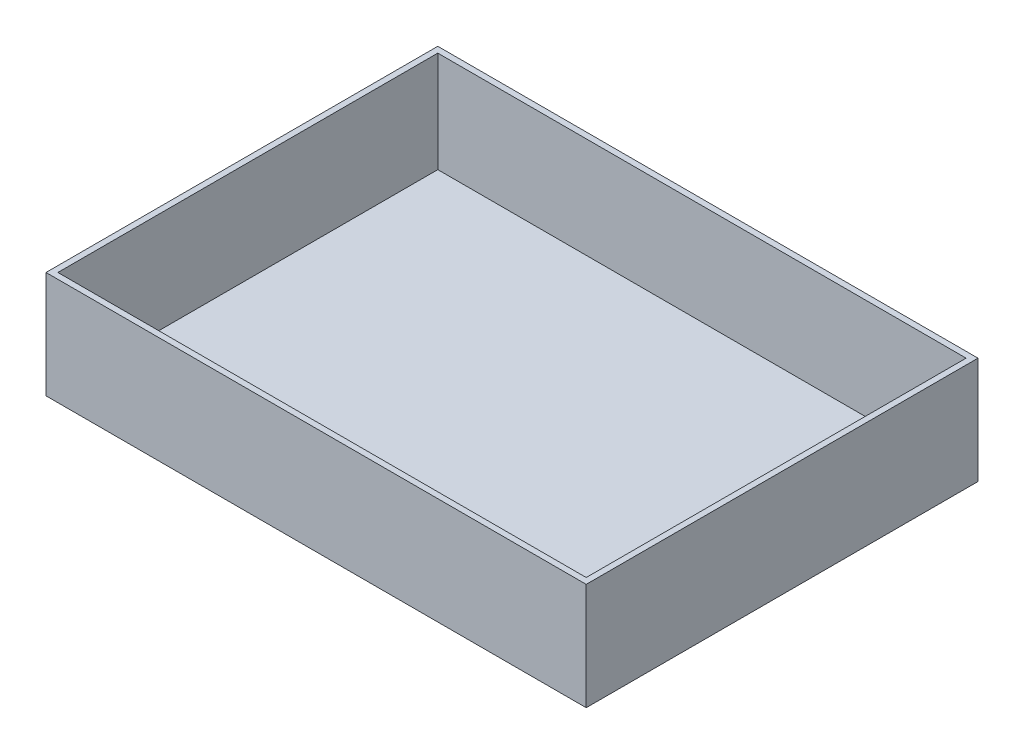
SolidWorks part; units mm, degrees
ref_plane "Front Plane" through (0, 0, 0) normal (0, 0, 1) x (1, 0, 0)
ref_plane "Top Plane" through (0, 0, 0) normal (0, 1, 0) x (1, 0, 0)
ref_plane "Right Plane" through (0, 0, 0) normal (1, 0, 0) x (0, 0, -1)
sketch "Sketch1" plane through (0, 0, 0) normal (0, 1, 0) x (1, 0, 0)
  line L1 (227.5, 165) -> (-227.5, 165)
  line L2 (227.5, 165) -> (227.5, -165)
  line L3 (227.5, -165) -> (-227.5, -165)
  line L4 (-227.5, 165) -> (-227.5, -165)
  line L5 (227.5, 165) -> (-227.5, -165) construction
  line L6 (227.5, -165) -> (-227.5, 165) construction
  point P0 (0, 0)
  dimension "D1" = 455
  dimension "D2" = 330
extrude "Boss-Extrude1" add sketch "Sketch1" against normal mid plane 90
shell "Shell1" thickness 5
